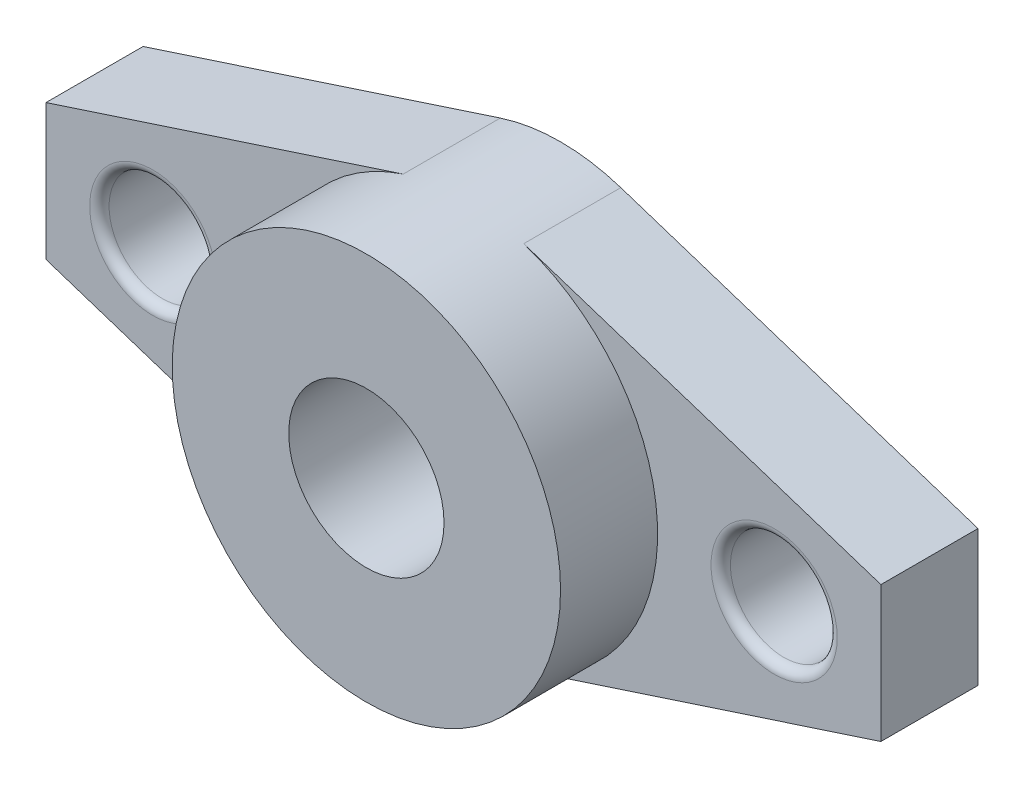
SolidWorks part; units mm, degrees
ref_plane "前视基准面" through (0, 0, 0) normal (0, 0, 1) x (1, 0, 0)
ref_plane "上视基准面" through (0, 0, 0) normal (0, 1, 0) x (1, 0, 0)
ref_plane "右视基准面" through (0, 0, 0) normal (1, 0, 0) x (0, 0, -1)
other "Configuration Table"
sketch "草图1" plane through (0, 0, 0) normal (0, 0, 1) x (1, 0, 0)
  line L0 (8.3884, 0) -> (14.0974, 0) construction
  line L1 (0, 0) -> (0, 3.8594) construction
  line L2 (-21.5, 3.5) -> (-21.5, -3.5)
  line L3 (21.5, 3.5) -> (21.5, -3.5)
  line L4 (-21.5, 3.5) -> (-3.1036, 9.5062)
  line L5 (21.5, 3.5) -> (3.1036, 9.5062)
  line L6 (21.5, -3.5) -> (3.1036, -9.5062)
  line L7 (-21.5, -3.5) -> (-3.1036, -9.5062)
  circle A0 centre (0, 0) radius 4
  circle A1 centre (0, 0) radius 10
  circle A2 centre (-16, 0) radius 2.75
  circle A3 centre (16, 0) radius 2.75
  point P18 (-21.5, 0)
  point P19 (21.5, 0)
  dimension "D1" = 8
  dimension "D2" = 20
  dimension "D3" = 5.5
  dimension "D4" = 5.5
  dimension "D6" = 16
  dimension "D8" = 16
  dimension "D5" = 21.5
  dimension "D7" = 21.5
  dimension "D9" = 7
  dimension "D10" = 7
extrude "凸台-拉伸1" add sketch "草图1" along normal blind 5 contours A1 L6 L3 L5 A3 | A1 L4 L2 L7 A2
sketch "草图2" plane through (0, 0, 0) normal (0, 0, 1) x (1, 0, 0)
  line L0 (-21.5, -3.5) -> (-3.1036, -9.5062) construction
  line L1 (-21.5, 3.5) -> (-21.5, -3.5) construction
  line L2 (-21.5, 3.5) -> (-3.1036, 9.5062) construction
  line L3 (21.5, -3.5) -> (3.1036, -9.5062) construction
  line L4 (21.5, 3.5) -> (21.5, -3.5) construction
  line L5 (21.5, 3.5) -> (3.1036, 9.5062) construction
  line L6 (-21.5, -3.5) -> (-3.1036, -9.5062)
  line L7 (-21.5, 3.5) -> (-21.5, -3.5)
  line L8 (-21.5, 3.5) -> (-3.1036, 9.5062)
  line L9 (21.5, -3.5) -> (3.1036, -9.5062)
  line L10 (21.5, 3.5) -> (21.5, -3.5)
  line L11 (21.5, 3.5) -> (3.1036, 9.5062)
  circle A1 centre (16, 0) radius 2.75
  circle A2 centre (16, 0) radius 2.75
  circle A3 centre (-16, 0) radius 2.75
  circle A4 centre (-16, 0) radius 2.75
  circle A5 centre (0, 0) radius 10
  circle A6 centre (0, 0) radius 10
  circle A7 centre (0, 0) radius 4
  circle A8 centre (0, 0) radius 4
  dimension "D1" = 0
  dimension "D2" = 0
  dimension "D3" = 0
  dimension "D4" = 0
extrude "凸台-拉伸2" add sketch "草图2" along normal blind 10 contours A6 A8
fillet "圆角2" radius 0.5 1 edges at (-13.25, 0, 5)
fillet "圆角3" radius 0.5 1 edges at (18.75, 0, 5)
